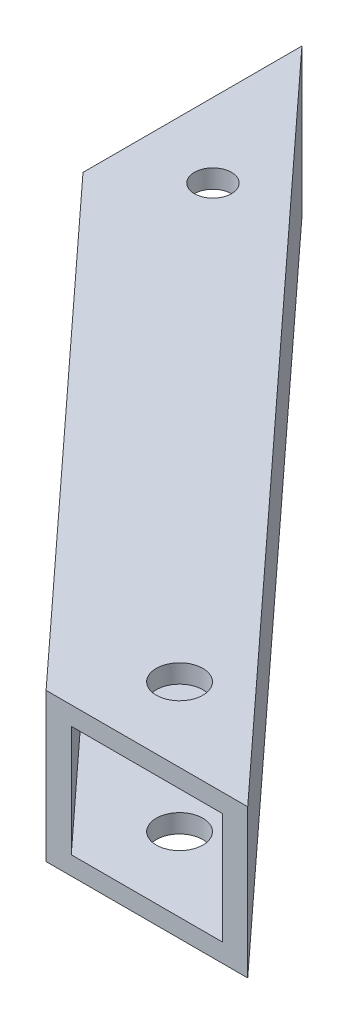
SolidWorks part; units mm, degrees
material "6061-T6 (SS)"
ref_plane "Front Plane" through (0, 0, 0) normal (0, 0, 1) x (1, 0, 0)
ref_plane "Top Plane" through (0, 0, 0) normal (0, 1, 0) x (1, 0, 0)
ref_plane "Right Plane" through (0, 0, 0) normal (1, 0, 0) x (0, 0, -1)
sketch "Sketch1" plane through (0, 0, 0) normal (0, 1, 0) x (1, 0, 0)
  line L0 (0, 0) -> (0, 117.475) construction
  line L1 (0, 0) -> (73.6599, 0) construction
  line L2 (108.1906, 0) -> (0, 117.475)
  line L3 (0, 117.475) -> (108.1906, 0)
  line L4 (0, 117.475) -> (-18.6836, 100.268)
  line L5 (108.1906, 0) -> (89.507, -17.207)
  line L6 (-18.6836, 100.268) -> (89.507, -17.207)
  line L7 (73.6599, 0) -> (108.1906, 0)
  dimension "D1" = 117.475
  dimension "D2" = 73.6599
  dimension "D3" = 25.4
extrude "Boss-Extrude3" add sketch "Sketch1" along normal blind 25.4 contours L4 L6 L5 L2
sketch "Sketch2" plane through (-58.5377, 0, -63.5637) normal (0.6774, 0, 0.7356) x (0.7356, 0, -0.6774)
  line L0 (54.1807, 25.4) -> (79.5807, 0) construction
  line L1 (79.5807, 0) -> (54.1807, 0) construction
  line L2 (57.3557, 3.175) -> (76.4057, 3.175)
  line L3 (57.3557, 3.175) -> (57.3557, 22.225)
  line L4 (57.3557, 22.225) -> (76.4057, 22.225)
  line L5 (76.4057, 3.175) -> (76.4057, 22.225)
  line L6 (57.3557, 3.175) -> (76.4057, 22.225) construction
  line L7 (57.3557, 22.225) -> (76.4057, 3.175) construction
  line L8 (79.5807, 25.4) -> (79.5807, 0) construction
  point P4 (66.8807, 12.7)
  dimension "D1" = 19.05
extrude "Cut-Extrude4" cut sketch "Sketch2" along normal up to surface (139.2362 mm away)
sketch "Sketch3" plane through (0, 25.4, 0) normal (0, 1, 0) x (1, 0, 0)
  line L0 (0, 117.475) -> (0, 79.981)
  line L1 (-18.6836, 100.268) -> (73.6599, 0) construction
  line L2 (0, 79.981) -> (-18.6836, 100.268)
  line L3 (-18.6836, 100.268) -> (0, 117.475)
  line L4 (108.1906, 0) -> (73.6599, 0)
  line L5 (73.6599, 0) -> (89.2506, -17.184)
  line L6 (89.2506, -17.184) -> (108.1906, 0)
  line L7 (-18.6836, 100.268) -> (73.6599, 0) construction
  line L8 (73.6599, 0) -> (108.1906, 0) construction
extrude "Cut-Extrude5" cut sketch "Sketch3" against normal blind 25.4
sketch "Sketch4" plane through (0, 25.4, 0) normal (0, 1, 0) x (1, 0, 0)
  line L0 (73.6599, 0) -> (73.6599, 37.494) construction
  line L1 (108.1906, 0) -> (0, 117.475) construction
  line L3 (73.6599, 0) -> (108.1906, 0) construction
  circle A0 centre (83.8199, 12.7) radius 3.9883
  dimension "D1" = 10.16
  dimension "D2" = 12.7
extrude "Cut-Extrude6" cut sketch "Sketch4" against normal blind 3.175
ref_plane "Plane1" through (0, 12.7, 0) normal (0, 1, 0) x (1, 0, 0)
mirror "Mirror1" about plane through (0, 12.7, 0) normal (0, 1, 0) of "Cut-Extrude6"
sketch "Sketch5" plane through (0, 0, 0) normal (0, -1, 0) x (1, 0, 0)
  line L0 (0, -79.981) -> (0, -117.475) construction
  circle A0 centre (12.7, -89.535) radius 3.175
  dimension "D1" = 6.35
  dimension "D2" = 12.7
  dimension "D3" = 27.94
extrude "Cut-Extrude7" cut sketch "Sketch5" against normal blind 3.175
mirror "Mirror2" about plane through (0, 12.7, 0) normal (0, 1, 0) of "Cut-Extrude7"
